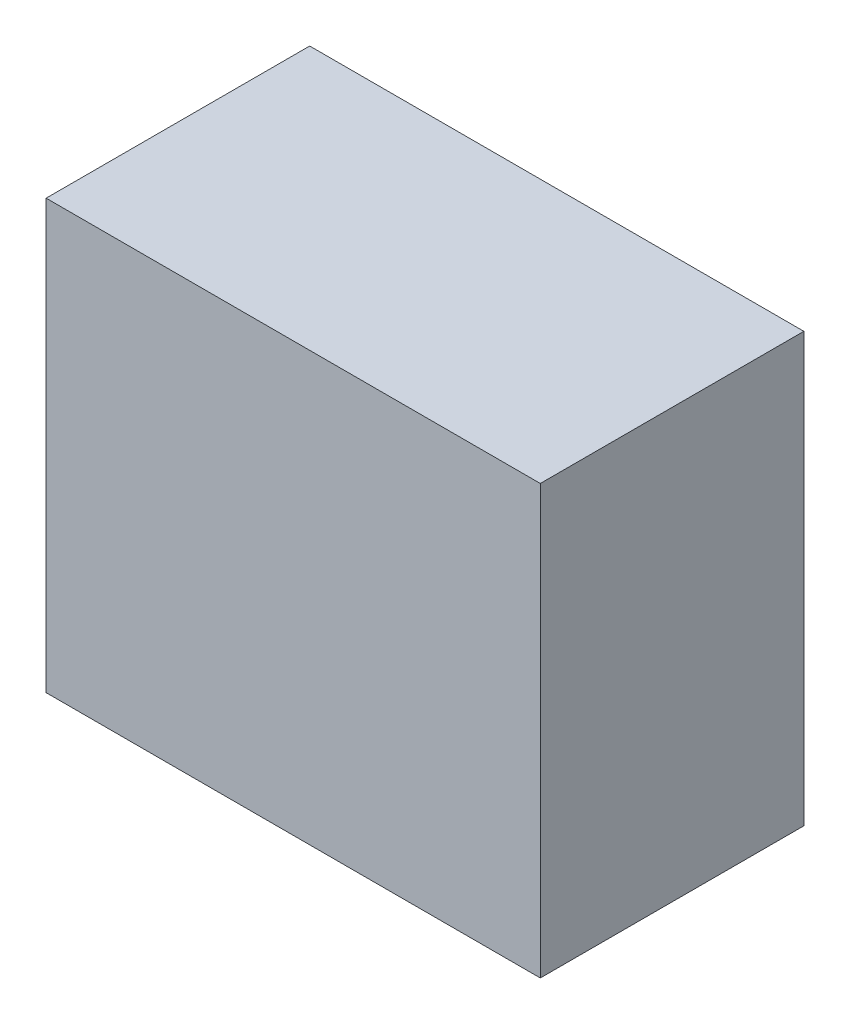
SolidWorks part; units mm, degrees
ref_plane "Front Plane" through (0, 0, 0) normal (0, 0, 1) x (1, 0, 0)
ref_plane "Top Plane" through (0, 0, 0) normal (0, 1, 0) x (1, 0, 0)
ref_plane "Right Plane" through (0, 0, 0) normal (1, 0, 0) x (0, 0, -1)
sketch "Sketch1" plane through (0, 0, 0) normal (0, 0, 1) x (1, 0, 0)
  line L1 (-482.1713, -309.7305) -> (-863.1713, -309.7305)
  line L2 (-482.1713, -309.7305) -> (-482.1713, 20.4695)
  line L3 (-482.1713, 20.4695) -> (-863.1713, 20.4695)
  line L4 (-863.1713, -309.7305) -> (-863.1713, 20.4695)
  point P4 (-672.6713, 20.4695)
  dimension "D1" = 381
  dimension "D2" = 330.2
extrude "Boss-Extrude1" add sketch "Sketch1" along normal blind 203.2
ref_plane "Plane1" through (-672.6713, 0, 0) normal (1, 0, 0) x (0, 0, -1)
